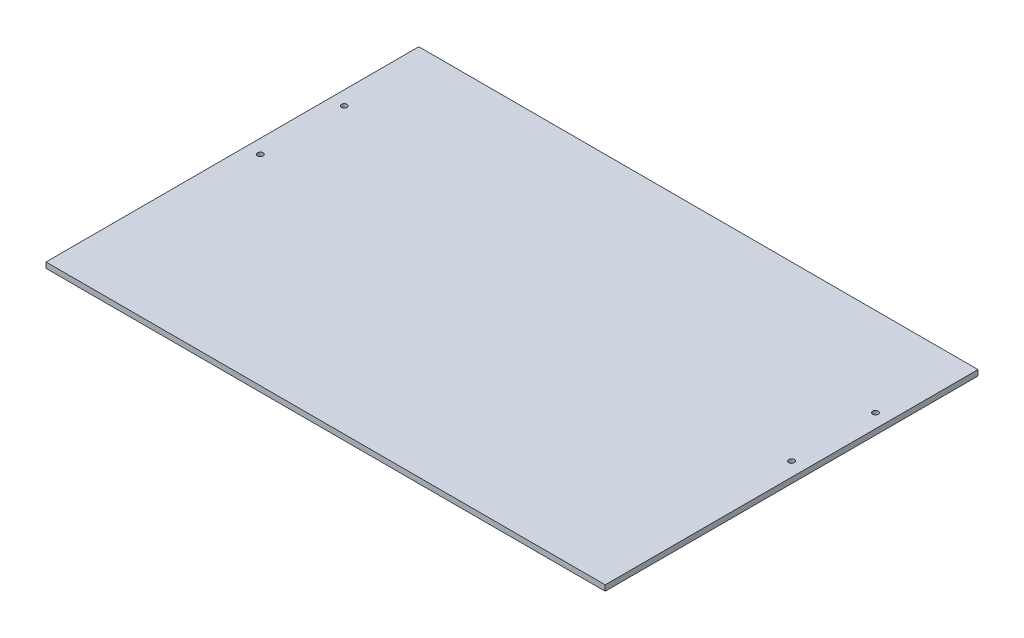
SolidWorks part; units mm, degrees
material "1023 Chapa de aço carbono (SS)"
ref_plane "Plano frontal" through (0, 0, 0) normal (0, 0, 1) x (1, 0, 0)
ref_plane "Plano superior" through (0, 0, 0) normal (0, 1, 0) x (1, 0, 0)
ref_plane "Plano direito" through (0, 0, 0) normal (1, 0, 0) x (0, 0, -1)
sketch "Esboço1" plane through (0, 0, 0) normal (0, 1, 0) x (1, 0, 0)
  line L0 (-142.5, 7.5) -> (-142.5, 52.5) construction
  line L1 (-150, -100) -> (150, -100)
  line L2 (-150, -100) -> (-150, 100)
  line L3 (-150, 100) -> (150, 100)
  line L4 (150, -100) -> (150, 100)
  line L5 (-150, -100) -> (150, 100) construction
  line L6 (-150, 100) -> (150, -100) construction
  line L7 (0, 100) -> (0, -100) construction
  line L8 (142.5, 7.5) -> (142.5, 52.5) construction
  circle A0 centre (-142.5, 52.5) radius 1.5
  circle A1 centre (-142.5, 7.5) radius 1.5
  circle A2 centre (142.5, 7.5) radius 1.5
  circle A3 centre (142.5, 52.5) radius 1.5
  point P0 (0, 0)
  point P12 (0, 0)
  point P20 (-142.5, 30)
  dimension "D4" = 3
  dimension "D1" = 200
  dimension "D2" = 300
  dimension "D3" = 45
  dimension "D5" = 7.5
  dimension "D6" = 70
extrude "Ressalto-extrusão1" add sketch "Esboço1" along normal blind 3
